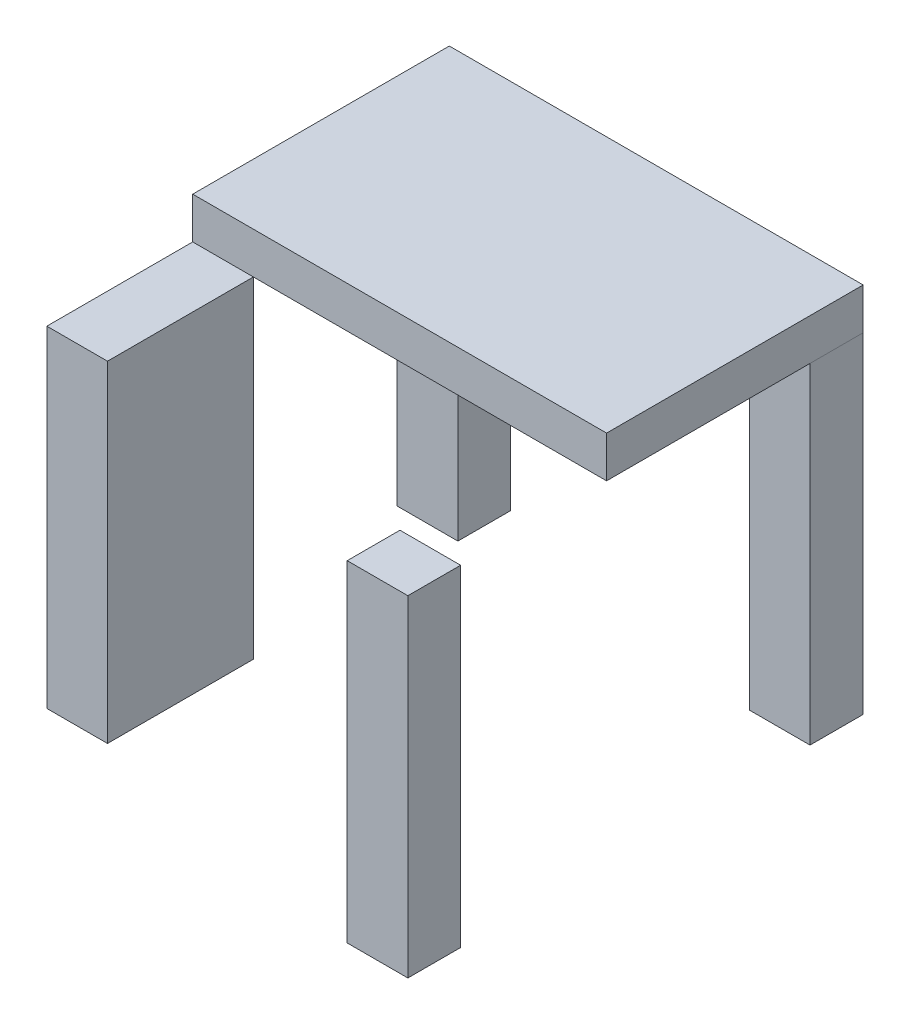
SolidWorks part; units mm, degrees
ref_plane "Front Plane" through (0, 0, 0) normal (0, 0, 1) x (1, 0, 0)
ref_plane "Top Plane" through (0, 0, 0) normal (0, 1, 0) x (1, 0, 0)
ref_plane "Right Plane" through (0, 0, 0) normal (1, 0, 0) x (0, 0, -1)
sketch "Sketch1" plane through (0, 0, 0) normal (0, 0, 1) x (1, 0, 0)
  line L1 (0, 0) -> (100, 0)
  line L2 (0, 0) -> (0, 10)
  line L3 (0, 10) -> (100, 10)
  line L4 (100, 0) -> (100, 10)
  dimension "D1" = 10
  dimension "D2" = 100
extrude "Boss-Extrude1" add sketch "Sketch1" along normal blind 62
sketch "Sketch2" plane through (0, 0, 0) normal (0, -1, 0) x (1, 0, 0)
  line L0 (85.3618, 110.0347) -> (100.0191, 110.0347)
  line L1 (0, 62) -> (14.6573, 62)
  line L2 (0, 62) -> (0, 97.2496)
  line L3 (0, 97.2496) -> (14.6573, 97.2496)
  line L4 (14.6573, 62) -> (14.6573, 97.2496)
  line L5 (85.3618, 110.0347) -> (85.3618, 97.2843)
  line L6 (85.3618, 97.2843) -> (100.0191, 97.2843)
  line L7 (100.0191, 110.0347) -> (100.0191, 97.2843)
  line L8 (-0.0191, 12.5688) -> (14.6382, 12.5688)
  line L9 (-0.0191, 12.5688) -> (-0.0191, -0.1816)
  line L10 (-0.0191, -0.1816) -> (14.6382, -0.1816)
  line L11 (14.6382, 12.5688) -> (14.6382, -0.1816)
  line L12 (85.2149, 12.7157) -> (99.8722, 12.7157)
  line L13 (85.2149, 12.7157) -> (85.2149, -0.0347)
  line L14 (85.2149, -0.0347) -> (99.8722, -0.0347)
  line L15 (99.8722, 12.7157) -> (99.8722, -0.0347)
extrude "Boss-Extrude2" add sketch "Sketch2" along normal blind 80
equation "\"LTest\" = 62mm"
equation "\"D1@Boss-Extrude1\"=\"LTest\""
